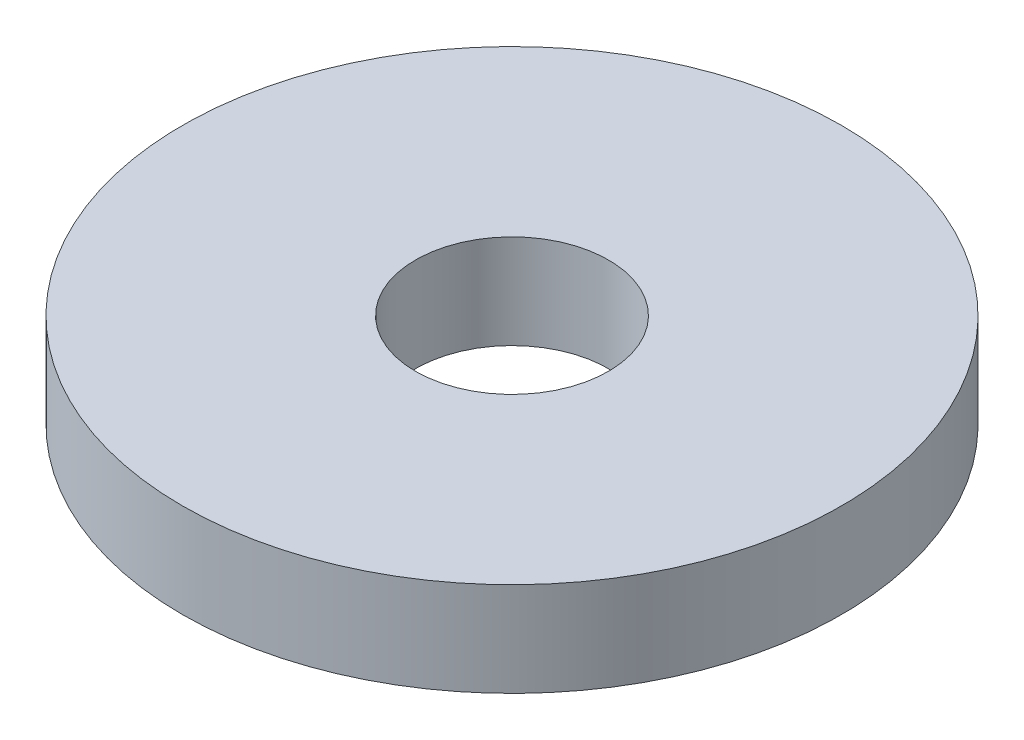
SolidWorks part; units mm, degrees
ref_plane "前视基准面" through (0, 0, 0) normal (0, 0, 1) x (1, 0, 0)
ref_plane "上视基准面" through (0, 0, 0) normal (0, 1, 0) x (1, 0, 0)
ref_plane "右视基准面" through (0, 0, 0) normal (1, 0, 0) x (0, 0, -1)
sketch "草图1" plane through (0, 0, 0) normal (0, 1, 0) x (1, 0, 0)
  circle A0 centre (0, 0) radius 35
  circle A1 centre (0, 0) radius 10.25
  dimension "D1" = 20.5
  dimension "D2" = 70
extrude "凸台-拉伸1" add sketch "草图1" along normal blind 10
equation "\"20.2、\"=117.08"
